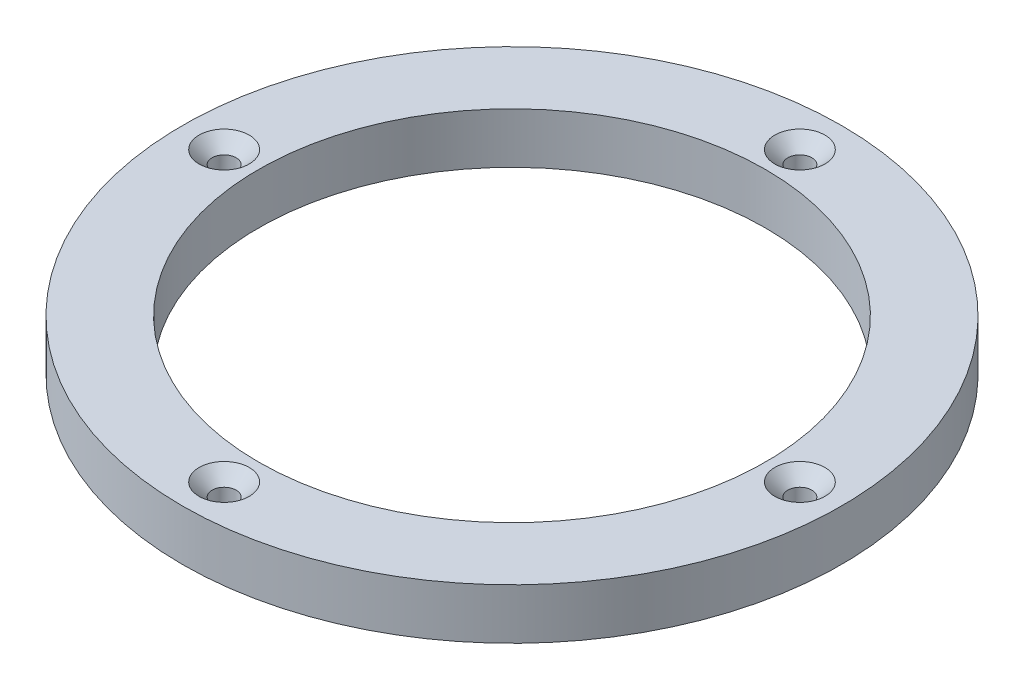
SolidWorks part; units mm, degrees
ref_plane "Front Plane" through (0, 0, 0) normal (0, 0, 1) x (1, 0, 0)
ref_plane "Top Plane" through (0, 0, 0) normal (0, 1, 0) x (1, 0, 0)
ref_plane "Right Plane" through (0, 0, 0) normal (1, 0, 0) x (0, 0, -1)
sketch "Sketch1" plane through (0, 0, 0) normal (0, 1, 0) x (1, 0, 0)
  circle A0 centre (0, 0) radius 61.7651
  circle A1 centre (0, 0) radius 47.5
  dimension "D1" = 123.5302
  dimension "D2" = 95
extrude "Boss-Extrude1" add sketch "Sketch1" along normal blind 9.5
sketch "Sketch7" plane through (0, 9.5, 0) normal (0, 1, 0) x (1, 0, 0)
  line L0 (-110.8198, 0) -> (121.244, 0) construction
  line L1 (0, 106.9347) -> (0, -114.3436) construction
  circle A0 centre (0, 0) radius 47.5 construction
  circle A1 centre (0, 0) radius 61.7651 construction
  circle A3 centre (0, 53.95) radius 2.25
  circle A4 centre (0, -53.95) radius 2.25
  circle A7 centre (53.95, 0) radius 2.25
  circle A8 centre (-53.95, 0) radius 2.25
  point P5 (0, 47.5)
  point P6 (0, 61.7651)
  point P14 (0, 47.5)
  point P16 (47.5, 0)
  point P17 (61.7651, 0)
  point P24 (-65.5279, 7.8278)
  dimension "D1" = 53.95
  dimension "D2" = 4.5
  dimension "D4" = 4.5
  dimension "D3" = 53.95
extrude "Cut-Extrude1" cut sketch "Sketch7" against normal blind 9.5
hole_wizard "CSK for M4 Countersunk Flat Head Screw1" positions "3DSketch2" profile "Sketch9" countersink size "M4" standard "ISO" end condition through all
sketch3d "3DSketch2"
  line L0 (0, 0, 53.95) -> (0, 9.5, 53.95) construction
  line L1 (-53.95, 0, 0) -> (-53.95, 9.5, 0) construction
  line L2 (0, 0, -53.95) -> (0, 9.5, -53.95) construction
  line L3 (53.95, 0, 0) -> (53.95, 9.5, 0) construction
  point P0 (0, 9.5, 53.95)
  point P4 (-53.95, 9.5, 0)
  point P8 (0, 9.5, -53.95)
  point P12 (53.95, 9.5, 0)
sketch "Sketch9" plane through (0, 9.5, 53.95) normal (1, 0, 0) x (0, 0, 1)
  line L0 (0, 0) -> (0, 9.5)
  line L1 (0, 9.5) -> (2.25, 9.5)
  line L2 (2.25, 9.5) -> (2.25, 2.45)
  line L3 (2.25, 2.45) -> (4.7, 0)
  line L5 (4.7, 0) -> (0, 0)
  line L6 (-2.25, 2.45) -> (-4.7, 0) construction
  line L11 (0, -6.35) -> (0, 107.95) construction
  dimension "Thru Hole Dia." = 4.5
  dimension "Thru Hole Depth" = 9.5
  dimension "Near C'Sink Dia." = 9.4
  dimension "Near C'Sink Angle" = 90
